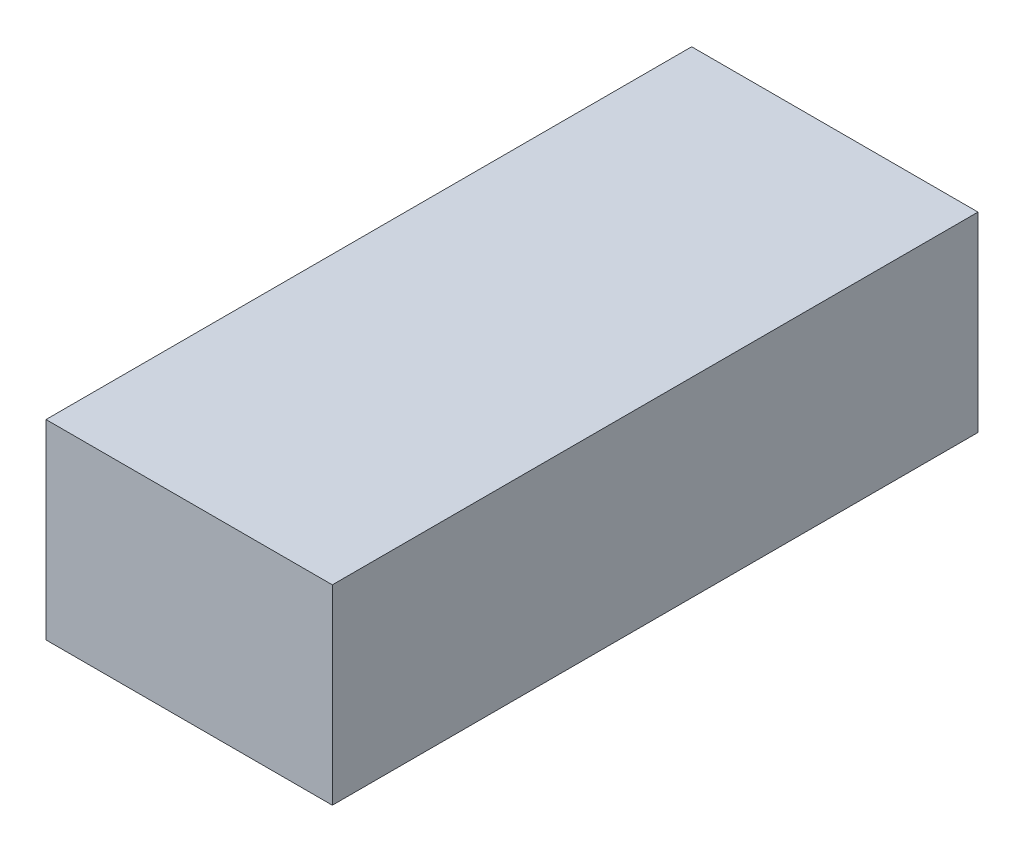
SolidWorks part; units mm, degrees
ref_plane "前视基准面" through (0, 0, 0) normal (0, 0, 1) x (1, 0, 0)
ref_plane "上视基准面" through (0, 0, 0) normal (0, 1, 0) x (1, 0, 0)
ref_plane "右视基准面" through (0, 0, 0) normal (1, 0, 0) x (0, 0, -1)
sketch "草图1" plane through (0, 0, 0) normal (0, 1, 0) x (1, 0, 0)
  line L1 (0, 0) -> (51, 0)
  line L2 (0, 0) -> (0, 115)
  line L3 (0, 115) -> (51, 115)
  line L4 (51, 0) -> (51, 115)
  dimension "D1" = 115
  dimension "D2" = 51
extrude "凸台-拉伸1" add sketch "草图1" along normal blind 34
